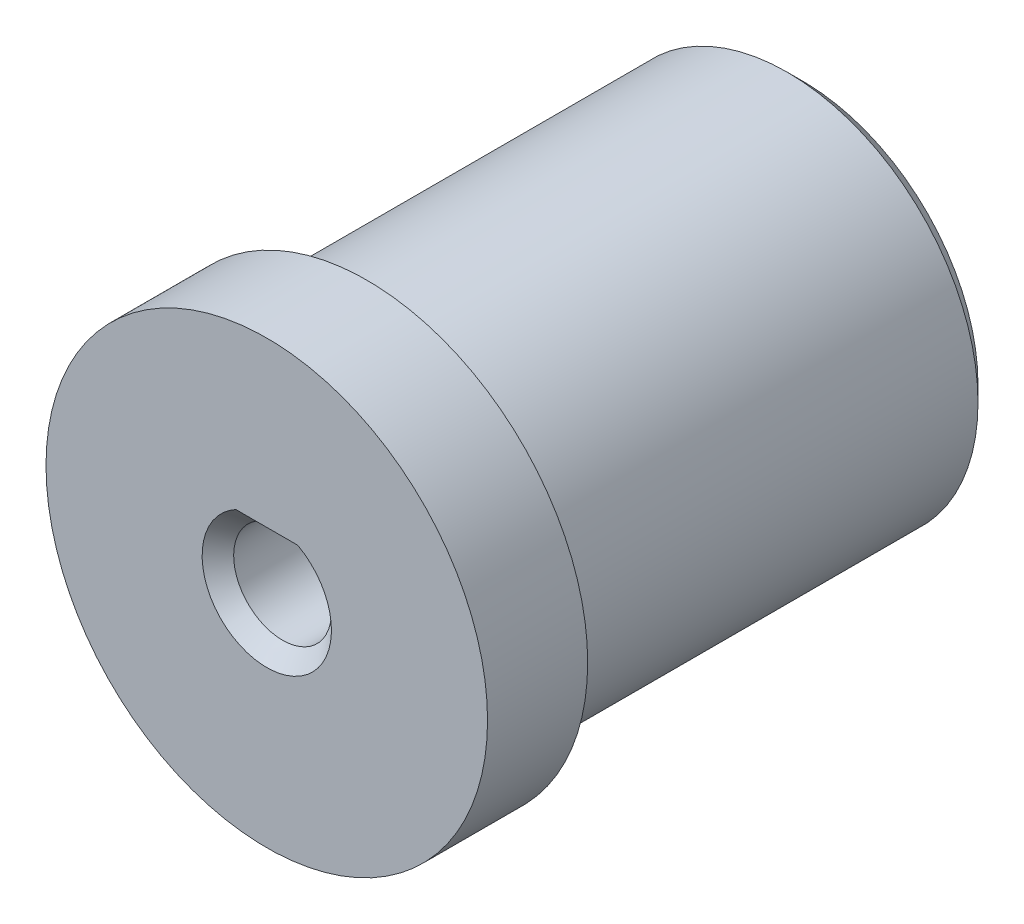
SolidWorks part; units mm, degrees
ref_plane "Front Plane" through (0, 0, 0) normal (0, 0, 1) x (1, 0, 0)
ref_plane "Top Plane" through (0, 0, 0) normal (0, 1, 0) x (1, 0, 0)
ref_plane "Right Plane" through (0, 0, 0) normal (1, 0, 0) x (0, 0, -1)
sketch "Sketch2" plane through (0, 0, 0) normal (0, 0, 1) x (1, 0, 0)
  line L0 (-1.6882, 2.6) -> (1.6882, 2.6)
  circle A0 centre (0, 0) radius 3.1
  circle A1 centre (0, 0) radius 12.1
  point P5 (0, 3.1)
  dimension "D1" = 6.2
  dimension "D3" = 24.2
  dimension "D2" = 0.5
extrude "Boss-Extrude1" add sketch "Sketch2" along normal blind 34 contours A1 A0 | L0 A0
sketch "Sketch3" plane through (0, 0, 34) normal (0, 0, 1) x (1, 0, 0)
  circle A0 centre (0, 0) radius 14
  arc M1 (1.6882, 2.6) -> (-1.6882, 2.6) centre (0, 0) cw
  line M2 (-1.6882, 2.6) -> (1.6882, 2.6)
  circle M3 centre (0, 0) radius 12.1
  dimension "D1" = 28
extrude "Boss-Extrude2" add sketch "Sketch3" against normal blind 6.35 contours M3 M2 M1 | A0 M3
chamfer "Chamfer1" distance 1 angle 45 5 edges at (0, 2.6, 0) (0, 2.6, 34) (0, -3.1, 0) (0, -3.1, 34) (12.1, 0, 0)
